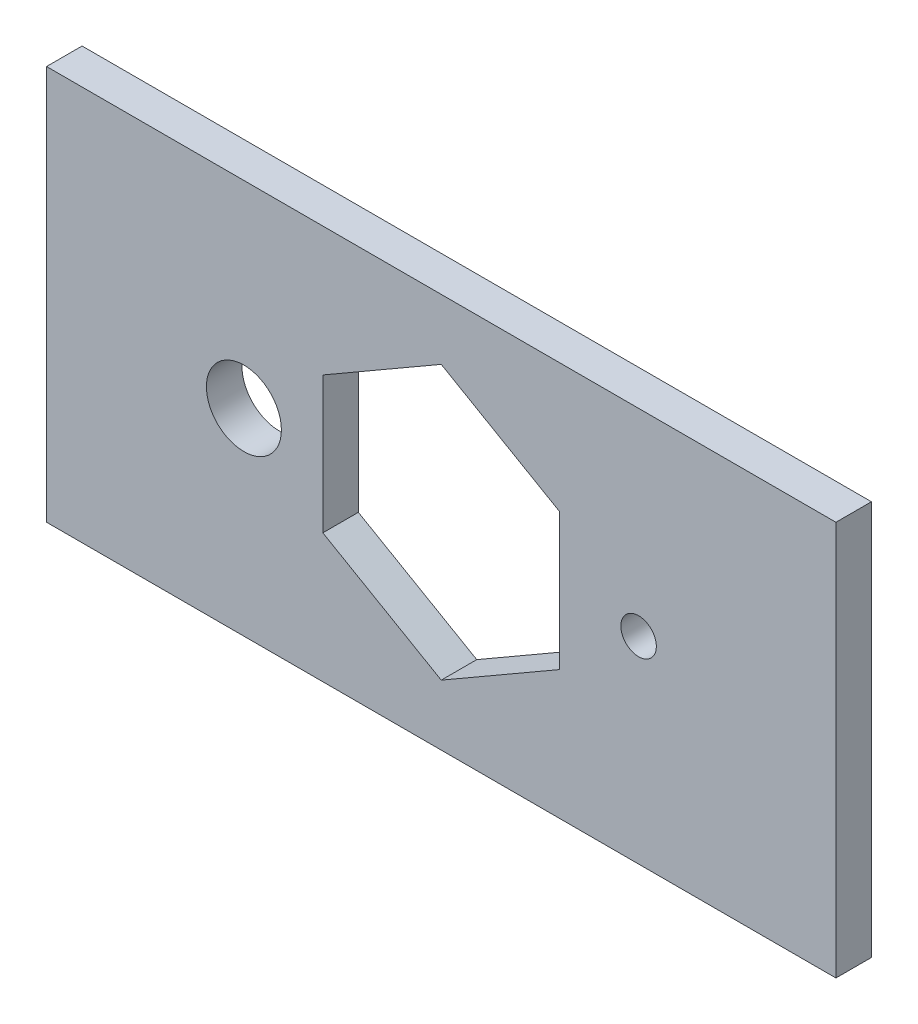
SolidWorks part; units mm, degrees
ref_plane "Front Plane" through (0, 0, 0) normal (0, 0, 1) x (1, 0, 0)
ref_plane "Top Plane" through (0, 0, 0) normal (0, 1, 0) x (1, 0, 0)
ref_plane "Right Plane" through (0, 0, 0) normal (1, 0, 0) x (0, 0, -1)
sketch "Sketch1" plane through (0, 0, 0) normal (0, 0, 1) x (1, 0, 0)
  line L1 (7.62, 4.3994) -> (0, 8.7988)
  line L2 (0, 8.7988) -> (-7.62, 4.3994)
  line L3 (-7.62, 4.3994) -> (-7.62, -4.3994)
  line L4 (-7.62, -4.3994) -> (0, -8.7988)
  line L5 (0, -8.7988) -> (7.62, -4.3994)
  line L6 (7.62, -4.3994) -> (7.62, 4.3994)
  line L7 (25.4, 12.7) -> (-25.4, 12.7)
  line L8 (25.4, 12.7) -> (25.4, -12.7)
  line L9 (25.4, -12.7) -> (-25.4, -12.7)
  line L10 (-25.4, 12.7) -> (-25.4, -12.7)
  circle A0 centre (0, 0) radius 7.62 construction
  circle A1 centre (-12.7, 0) radius 2.413
  circle A2 centre (12.7, 0) radius 1.143
  circle A3 centre (0, 0) radius 7.9375 construction
  dimension "D9" = 4.826
  dimension "D10" = 2.286
  dimension "D11" = 15.875
  dimension "D2" = 25.4
  dimension "D3" = 50.8
  dimension "D4" = 25.4
  dimension "D5" = 12.7
  dimension "D6" = 12.7
  dimension "D7" = 12.7
  dimension "D8" = 25.4
  dimension "D12" = 15.24
extrude "Boss-Extrude1" add sketch "Sketch1" along normal mid plane 2.286
